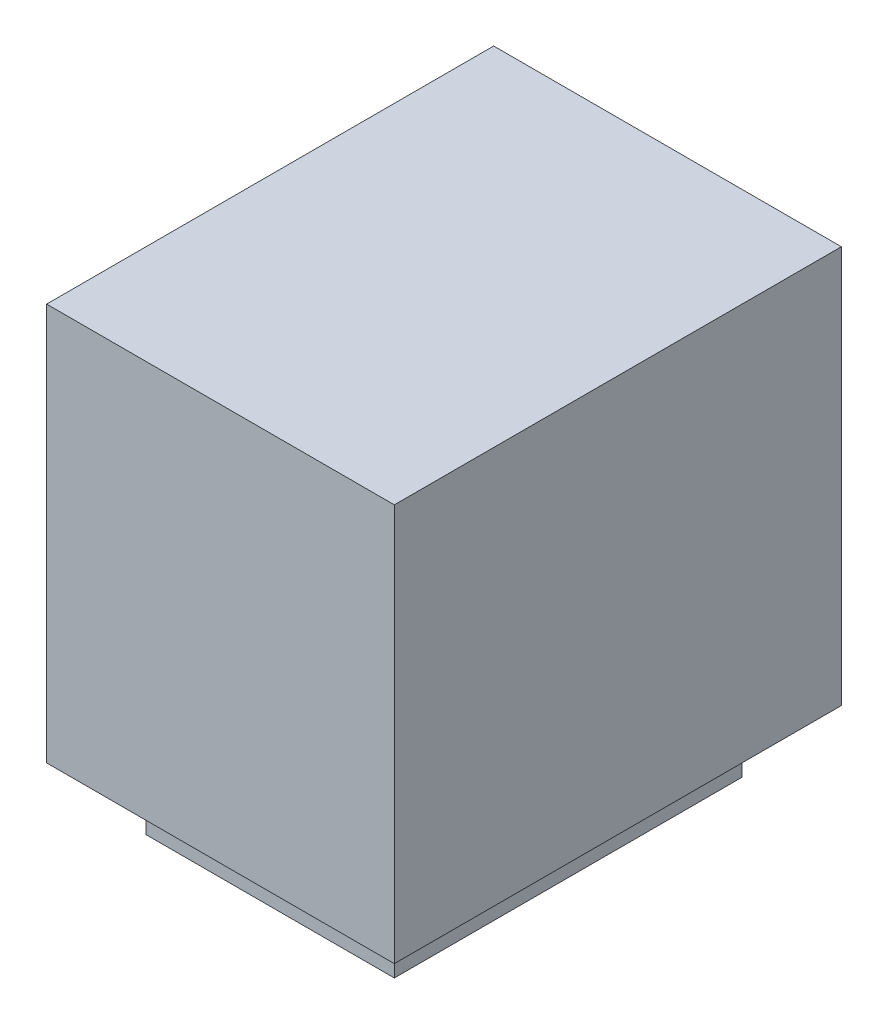
SolidWorks part; units mm, degrees
material "A286 Iron Base Superalloy"
ref_plane "Front Plane" through (0, 0, 0) normal (0, 0, 1) x (1, 0, 0)
ref_plane "Top Plane" through (0, 0, 0) normal (0, 1, 0) x (1, 0, 0)
ref_plane "Right Plane" through (0, 0, 0) normal (1, 0, 0) x (0, 0, -1)
sketch "Sketch1" plane through (0, 0, 0) normal (0, 1, 0) x (1, 0, 0)
  line L0 (0, -1000) -> (0, 49000) construction
  line L1 (-1000, 0) -> (49000, 0) construction
  line L3 (-700, 900) -> (700, 900)
  line L4 (-700, 900) -> (-700, -900)
  line L5 (-700, -900) -> (700, -900)
  line L6 (700, 900) -> (700, -900)
  line L7 (0, -900) -> (0, 900) construction
  line L8 (-700, 0) -> (700, 0) construction
  point P4 (0, 0)
  dimension "D1" = 1800
  dimension "D2" = 1400
extrude "Boss-Extrude1" add sketch "Sketch1" along normal blind 1600
sketch "Sketch2" plane through (0, 0, 0) normal (0, 1, 0) x (1, 0, 0)
  line L1 (-500, 700) -> (500, 700)
  line L2 (-500, 700) -> (-500, -700)
  line L3 (-500, -700) -> (500, -700)
  line L4 (500, 700) -> (500, -700)
  line L5 (0, -700) -> (0, 700) construction
  line L6 (-500, 0) -> (500, 0) construction
  point P0 (0, 0)
  dimension "D1" = 1400
  dimension "D2" = 1000
extrude "Boss-Extrude2" add sketch "Sketch2" against normal blind 250
sketch "Sketch3" plane through (0, 0, 0) normal (0, 0, 1) x (1, 0, 0)
  line L1 (-392.1371, 1300.8068) -> (407.8629, 1300.8068)
  line L2 (-392.1371, 1300.8068) -> (-392.1371, 300.8068)
  line L3 (-392.1371, 300.8068) -> (407.8629, 300.8068)
  line L4 (407.8629, 1300.8068) -> (407.8629, 300.8068)
  line L5 (7.8629, 300.8068) -> (7.8629, 1300.8068) construction
  line L6 (-392.1371, 800.8068) -> (407.8629, 800.8068) construction
  point P0 (7.8629, 800.8068)
  point P4 (-43.2461, 824.3955)
  point P5 (7.8629, 800.8068)
  dimension "D1" = 800
  dimension "D2" = 1000
extrude "Cut-Extrude1" cut sketch "Sketch3" against normal blind 50
sketch "Sketch4" plane through (0, 0, 0) normal (0, 0, 1) x (1, 0, 0)
  line L1 (-226.4112, 999.3955) -> (273.5888, 999.3955)
  line L2 (-226.4112, 999.3955) -> (-226.4112, 649.3955)
  line L3 (-226.4112, 649.3955) -> (273.5888, 649.3955)
  line L4 (273.5888, 999.3955) -> (273.5888, 649.3955)
  line L5 (23.5888, 649.3955) -> (23.5888, 999.3955) construction
  line L6 (-226.4112, 824.3955) -> (273.5888, 824.3955) construction
  point P0 (23.5888, 824.3955)
  point P4 (23.5888, 824.3955)
  dimension "D1" = 350
  dimension "D2" = 500
extrude "Boss-Extrude3" add sketch "Sketch4" against normal blind 50
sketch "Sketch5" plane through (0, 0, -900) normal (0, 0, -1) x (-1, 0, 0)
  line L1 (-132.8629, 997.9843) -> (117.1371, 997.9843)
  line L2 (-132.8629, 997.9843) -> (-132.8629, 697.9843)
  line L3 (-132.8629, 697.9843) -> (117.1371, 697.9843)
  line L4 (117.1371, 997.9843) -> (117.1371, 697.9843)
  line L5 (-7.8629, 697.9843) -> (-7.8629, 997.9843) construction
  line L6 (-132.8629, 847.9843) -> (117.1371, 847.9843) construction
  point P0 (-7.8629, 847.9843)
  dimension "D1" = 250
  dimension "300" = 300
